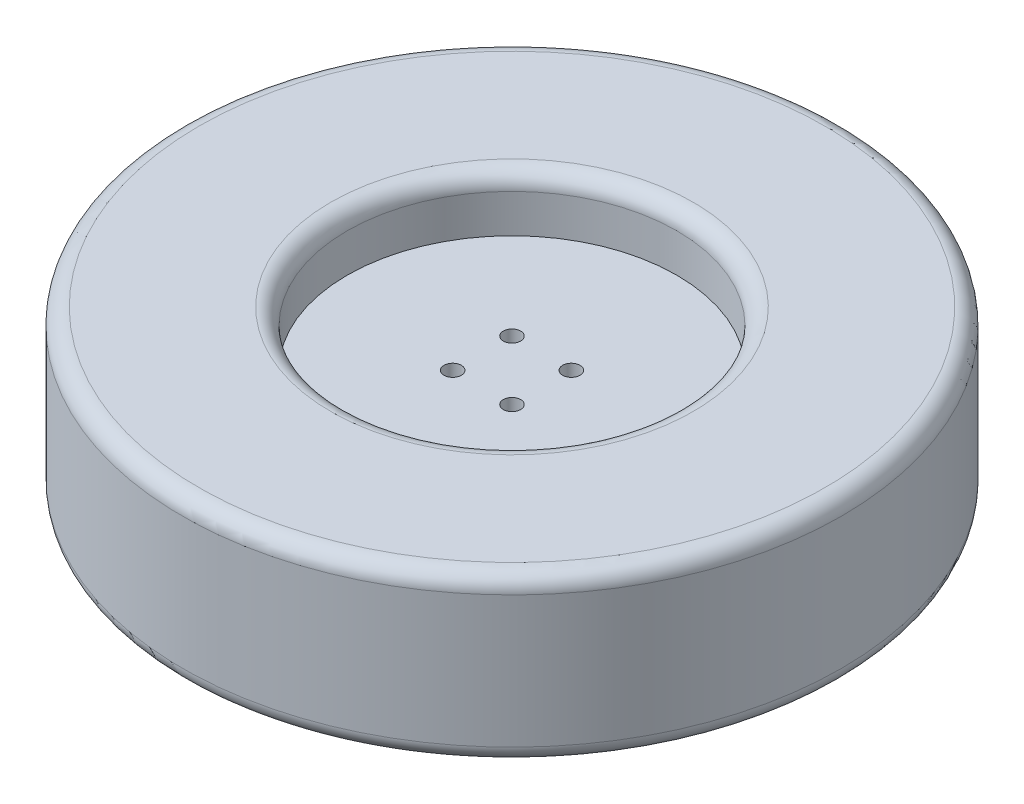
SolidWorks part; units mm, degrees
ref_plane "Front Plane" through (0, 0, 0) normal (0, 0, 1) x (1, 0, 0)
ref_plane "Top Plane" through (0, 0, 0) normal (0, 1, 0) x (1, 0, 0)
ref_plane "Right Plane" through (0, 0, 0) normal (1, 0, 0) x (0, 0, -1)
sketch "Wheel Cross Section" plane through (0, 0, 0) normal (0, 0, 1) x (1, 0, 0)
  line L0 (-32.7969, 0) -> (-57.15, 0) construction
  line L5 (0, 6.35) -> (0, -6.35)
  line L6 (0, 6.35) -> (-38.1, 6.35)
  line L7 (55, 0) -> (-55, 0) construction
  line L8 (0, -6.35) -> (-38.1, -6.35)
  line L9 (-38.1, -19.05) -> (-76.2, -19.05)
  line L10 (-38.1, -19.05) -> (-38.1, -6.35)
  line L11 (-38.1, 19.05) -> (-76.2, 19.05)
  line L12 (-76.2, -19.05) -> (-76.2, 19.05)
  line L13 (-38.1, -19.05) -> (-76.2, 19.05) construction
  line L14 (-38.1, 19.05) -> (-76.2, -19.05) construction
  line L15 (-38.1, 6.35) -> (-38.1, 19.05)
  point P0 (0, 0)
  point P1 (0, 0)
  point P4 (0, 0)
  dimension "D1" = 38.1
  dimension "D2" = 38.1
  dimension "D3" = 12.7
  dimension "D4" = 38.1
  dimension "D5" = 12.7
revolve "Main Wheel Rev" add sketch "Wheel Cross Section" angle 360 about L5
fillet "Wheel Edges Fillet" radius 3.81 4 edges at (-76.2, -19.05, 0) (-76.2, 19.05, 0) (-38.1, -19.05, 0) (-38.1, 19.05, 0)
sketch "Sketch2" plane through (0, 6.35, 0) normal (0, 1, 0) x (1, 0, 0)
  line L1 (-6.858, -6.858) -> (6.858, -6.858) construction
  line L2 (-6.858, -6.858) -> (-6.858, 6.858) construction
  line L3 (-6.858, 6.858) -> (6.858, 6.858) construction
  line L4 (6.858, -6.858) -> (6.858, 6.858) construction
  line L5 (-6.858, -6.858) -> (6.858, 6.858) construction
  line L6 (-6.858, 6.858) -> (6.858, -6.858) construction
  circle A0 centre (-6.858, 6.858) radius 2.0066
  circle A1 centre (6.858, 6.858) radius 2.0066
  circle A2 centre (6.858, -6.858) radius 2.0066
  circle A3 centre (-6.858, -6.858) radius 2.0066
  point P0 (0, 0)
  dimension "D3" = 4.0132
  dimension "D1" = 13.716
  dimension "D2" = 13.716
extrude "4 Mounting Holes" cut sketch "Sketch2" against normal blind 12.7
